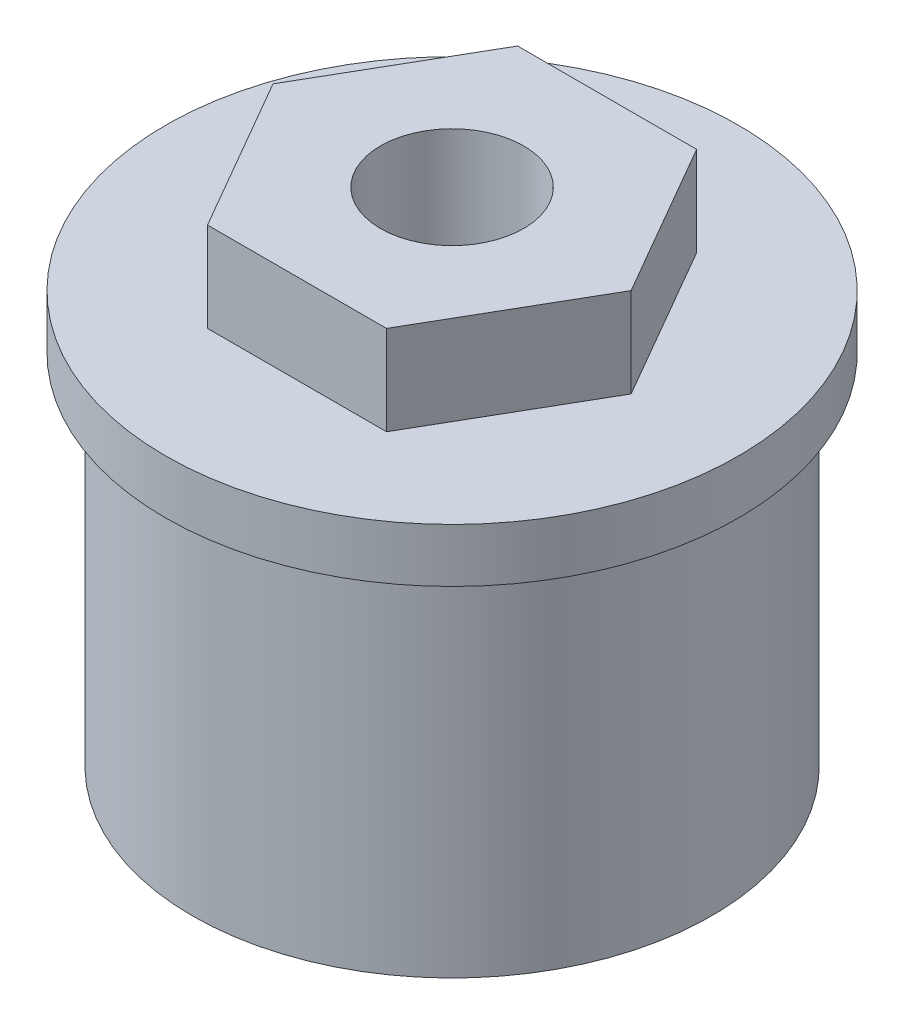
SolidWorks part; units mm, degrees
ref_plane "Front Plane" through (0, 0, 0) normal (0, 0, 1) x (1, 0, 0)
ref_plane "Top Plane" through (0, 0, 0) normal (0, 1, 0) x (1, 0, 0)
ref_plane "Right Plane" through (0, 0, 0) normal (1, 0, 0) x (0, 0, -1)
sketch "Sketch1" plane through (0, 0, 0) normal (0, 1, 0) x (1, 0, 0)
  circle A0 centre (0, 0) radius 14.5
  dimension "D1" = 29
extrude "Boss-Extrude1" add sketch "Sketch1" along normal blind 20
sketch "Sketch2" plane through (0, 20, 0) normal (0, 1, 0) x (1, 0, 0)
  circle A0 centre (0, 0) radius 16
  dimension "D1" = 32
extrude "Boss-Extrude2" add sketch "Sketch2" along normal blind 3
sketch "Sketch3" plane through (0, 23, 0) normal (0, 1, 0) x (1, 0, 0)
  line L1 (10, 0) -> (5, 8.6603)
  line L2 (5, 8.6603) -> (-5, 8.6603)
  line L3 (-5, 8.6603) -> (-10, 0)
  line L4 (-10, 0) -> (-5, -8.6603)
  line L5 (-5, -8.6603) -> (5, -8.6603)
  line L6 (5, -8.6603) -> (10, 0)
  circle A0 centre (0, 0) radius 8.6603 construction
  dimension "D1" = 10
extrude "Boss-Extrude3" add sketch "Sketch3" along normal blind 5
sketch "Sketch4" plane through (0, 28, 0) normal (0, 1, 0) x (1, 0, 0)
  circle A0 centre (0, 0) radius 4
  dimension "D1" = 8
extrude "Cut-Extrude1" cut sketch "Sketch4" against normal blind 30
